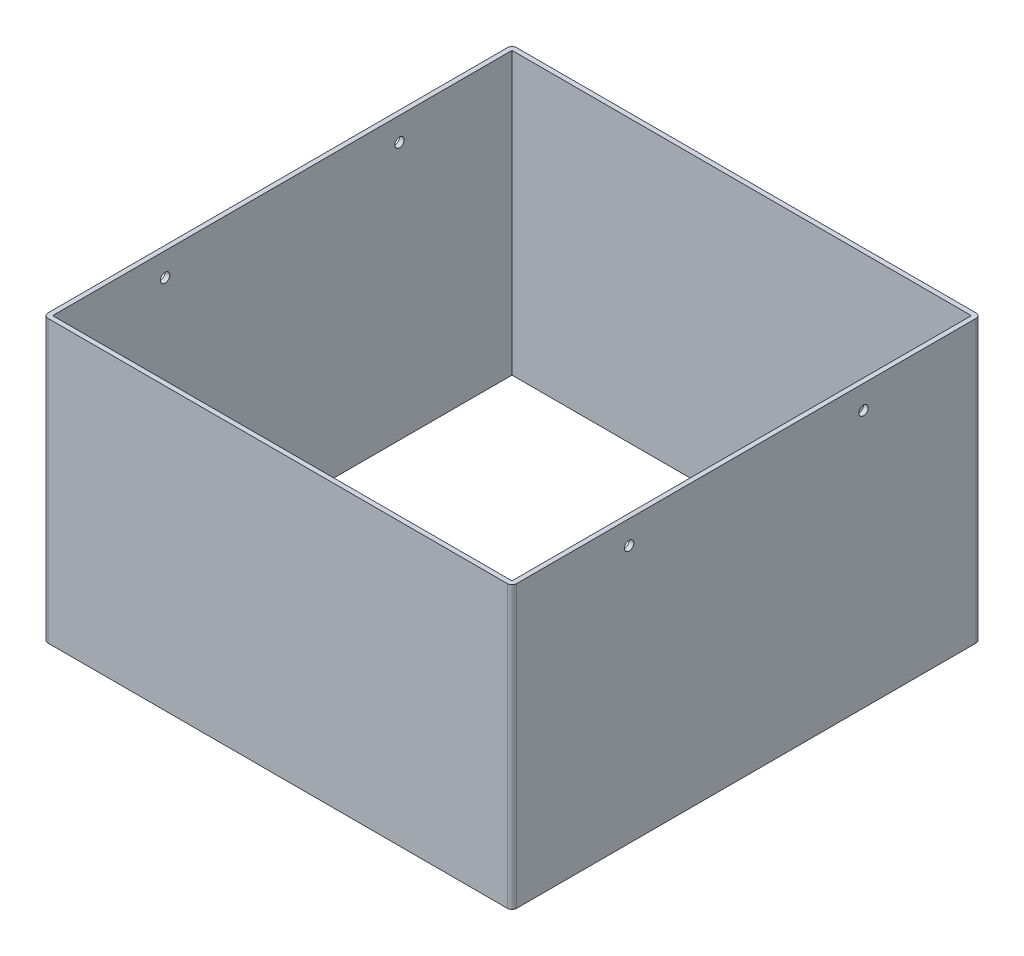
SolidWorks part; units mm, degrees
ref_plane "Front Plane" through (0, 0, 0) normal (0, 0, 1) x (1, 0, 0)
ref_plane "Top Plane" through (0, 0, 0) normal (0, 1, 0) x (1, 0, 0)
ref_plane "Right Plane" through (0, 0, 0) normal (1, 0, 0) x (0, 0, -1)
sketch "Sketch1" plane through (0, 0, 0) normal (0, 1, 0) x (1, 0, 0)
  line L1 (-50, 50) -> (50, 50)
  line L2 (-50, 50) -> (-50, -50)
  line L3 (-50, -50) -> (50, -50)
  line L4 (50, 50) -> (50, -50)
  line L5 (-50, 50) -> (50, -50) construction
  line L6 (-50, -50) -> (50, 50) construction
  point P0 (0, 0)
  dimension "D1" = 100
  dimension "D2" = 100
extrude "Boss-Extrude1" add sketch "Sketch1" along normal blind 60
sketch "Sketch2" plane through (0, 60, 0) normal (0, 1, 0) x (1, 0, 0)
  line L1 (-49, 49) -> (49, 49)
  line L2 (-49, 49) -> (-49, -49)
  line L3 (-49, -49) -> (49, -49)
  line L4 (49, 49) -> (49, -49)
  line L5 (-49, 49) -> (49, -49) construction
  line L6 (-49, -49) -> (49, 49) construction
  point P0 (0, 0)
  dimension "D1" = 98
  dimension "D2" = 98
extrude "Cut-Extrude1" cut sketch "Sketch2" against normal blind 225
sketch "Sketch3" plane through (-50, 0, 0) normal (-1, 0, 0) x (0, 0, 1)
  line L0 (50, 60) -> (50, 0) construction
  line L8 (-50, 50) -> (-49, 50) construction
  line L10 (0, 60) -> (0, 50)
  line L11 (-50, 60) -> (50, 60)
  line L16 (-50, 60) -> (-50, 50)
  line L17 (-50, 50) -> (50, 50)
  line L18 (50, 60) -> (50, 50)
  line L19 (0, 55) -> (-50, 55)
  circle A4 centre (-25, 55) radius 1
  circle A5 centre (25, 55) radius 1
  point P10 (0, 55)
extrude "Cut-Extrude2" cut sketch "Sketch3" against normal blind 118 contours L19 A4 | A5
fillet "Fillet1" radius 1 4 edges at (-50, 30, 50) (50, 30, 50) (50, 30, -50) (-50, 30, -50)
